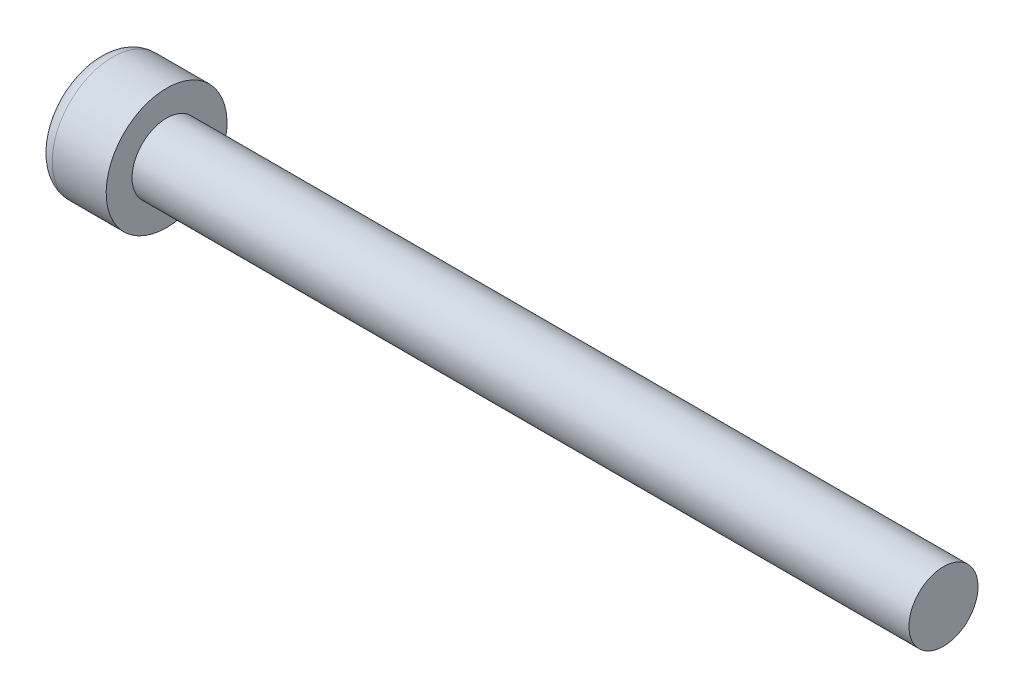
SolidWorks part; units mm, degrees
material "Plain Carbon Steel"
ref_plane "Front Plane" through (0, 0, 0) normal (0, 0, 1) x (1, 0, 0)
ref_plane "Top Plane" through (0, 0, 0) normal (0, 1, 0) x (1, 0, 0)
ref_plane "Right Plane" through (0, 0, 0) normal (1, 0, 0) x (0, 0, -1)
sketch "Sketch1" plane through (0, 0, 0) normal (0, 0, 1) x (1, 0, 0)
  line L0 (0, 0) -> (0, 2.625)
  line L1 (0.875, 3.5) -> (4, 3.5)
  line L2 (4, 3.5) -> (4, 2)
  line L3 (4, 2) -> (49, 2)
  line L4 (49, 2) -> (49, 0)
  line L5 (49, 0) -> (0, 0) construction
  line L6 (0.875, 2.625) -> (0.875, 1.75) construction
  line L7 (0.875, 1.75) -> (0.875, 0.875) construction
  line L8 (0.875, 0.875) -> (0.875, 0) construction
  line L9 (0.875, 3.5) -> (0.875, 2.625) construction
  line L10 (0, 0) -> (49, 0)
  arc A0 (0, 2.625) -> (0.875, 3.5) centre (0.875, 2.625) cw
  dimension "D1" = 4
  dimension "D2" = 7
  dimension "D3" = 4
  dimension "D4" = 45
revolve "Revolve1" add sketch "Sketch1" angle 360 about L10
sketch "Sketch2" plane through (0, 0, 0) normal (-1, 0, 0) x (0, 0, 1)
  line L1 (0, 1.7321) -> (-1.5, 0.866)
  line L2 (-1.5, 0.866) -> (-1.5, -0.866)
  line L3 (-1.5, -0.866) -> (0, -1.7321)
  line L4 (0, -1.7321) -> (1.5, -0.866)
  line L5 (1.5, -0.866) -> (1.5, 0.866)
  line L6 (1.5, 0.866) -> (0, 1.7321)
  circle A0 centre (0, 0) radius 1.5 construction
  dimension "D1" = 3
extrude "Cut-Extrude1" cut sketch "Sketch2" against normal blind 2
